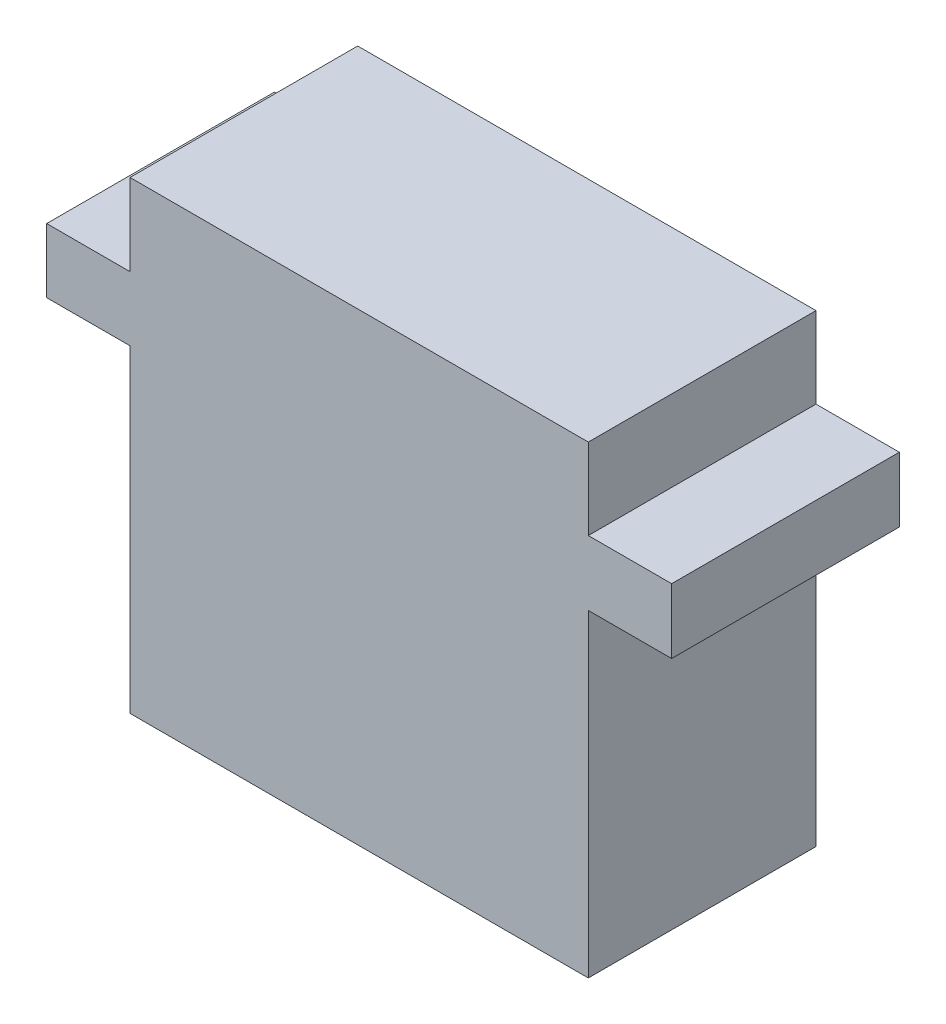
SolidWorks part; units mm, degrees
ref_plane "Front Plane" through (0, 0, 0) normal (0, 0, 1) x (1, 0, 0)
ref_plane "Top Plane" through (0, 0, 0) normal (0, 1, 0) x (1, 0, 0)
ref_plane "Right Plane" through (0, 0, 0) normal (1, 0, 0) x (0, 0, -1)
sketch "Sketch2" plane through (0, 0, 0) normal (0, 1, 0) x (1, 0, 0)
  line L1 (0, 0) -> (39.878, 0)
  line L2 (0, 0) -> (0, 19.812)
  line L3 (0, 19.812) -> (39.878, 19.812)
  line L4 (39.878, 0) -> (39.878, 19.812)
  dimension "D1" = 39.878
  dimension "D2" = 19.812
extrude "Boss-Extrude1" add sketch "Sketch2" along normal blind 40.386
sketch "Sketch3" plane through (39.878, 0, 0) normal (1, 0, 0) x (0, 0, -1)
  line L0 (0, 40.386) -> (0, 0) construction
  line L1 (0, 27.7) -> (19.812, 27.7)
  line L2 (0, 27.7) -> (0, 33.3401)
  line L3 (0, 33.3401) -> (19.812, 33.3401)
  line L4 (19.812, 27.7) -> (19.812, 33.3401)
  line L5 (19.812, 40.386) -> (19.812, 0) construction
  line L6 (0, 0) -> (19.812, 0) construction
  dimension "D1" = 5.6401
  dimension "D2" = 27.7
extrude "Boss-Extrude2" add sketch "Sketch3" along normal blind 7.25
sketch "Sketch4" plane through (0, 0, 0) normal (-1, 0, 0) x (0, 0, 1)
  line L0 (-19.812, 40.386) -> (-19.812, 0) construction
  line L1 (-19.812, 27.7) -> (0, 27.7)
  line L2 (-19.812, 27.7) -> (-19.812, 33.288)
  line L3 (-19.812, 33.288) -> (0, 33.288)
  line L4 (0, 27.7) -> (0, 33.288)
  line L5 (0, 40.386) -> (0, 0) construction
  line L6 (-19.812, 0) -> (0, 0) construction
  dimension "D1" = 5.588
  dimension "D2" = 27.7
extrude "Boss-Extrude3" add sketch "Sketch4" along normal blind 7.25
